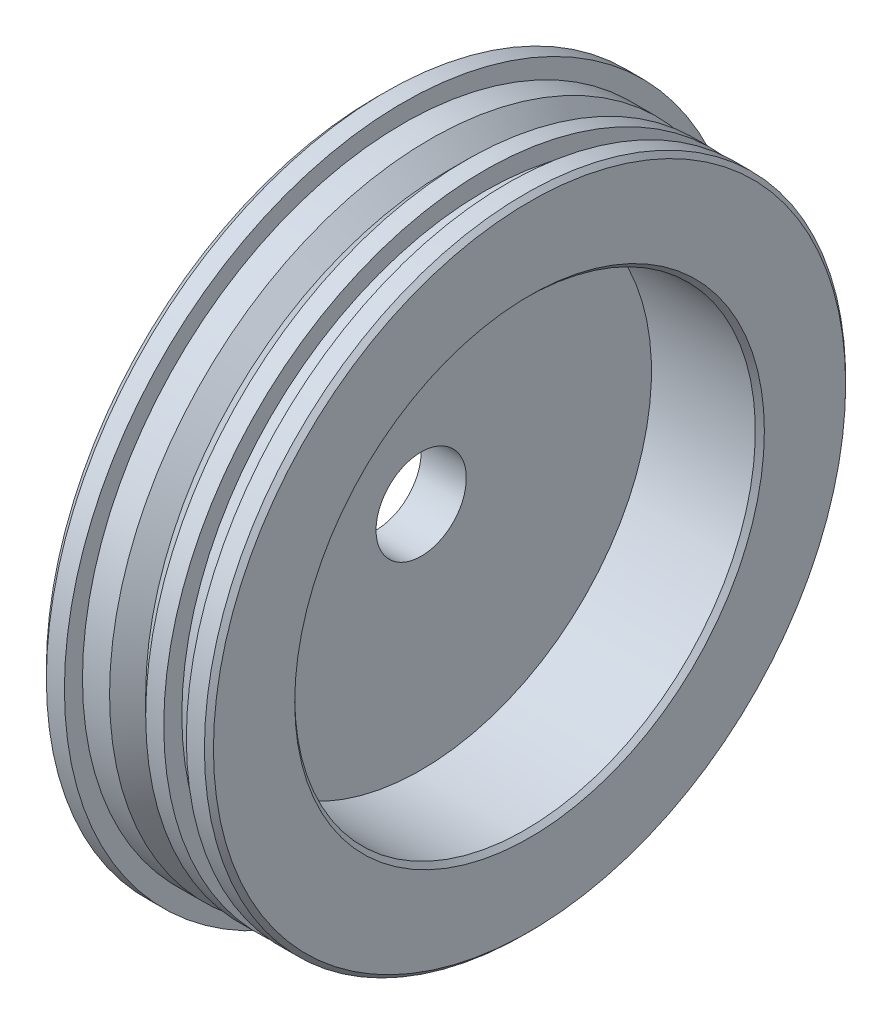
SolidWorks part; units mm, degrees
material "1060 Сплав"
ref_plane "Спереди" through (0, 0, 0) normal (0, 0, 1) x (1, 0, 0)
ref_plane "Сверху" through (0, 0, 0) normal (0, 1, 0) x (1, 0, 0)
ref_plane "Справа" through (0, 0, 0) normal (1, 0, 0) x (0, 0, -1)
sketch "Эскиз1" plane through (0, 0, 0) normal (0, 0, 1) x (1, 0, 0)
  line L0 (0, 0) -> (75.9362, 0) construction
  line L1 (-5, 0) -> (-5, 36.5)
  line L2 (-4, 37.5) -> (-2, 37.5)
  line L3 (-2, 37.5) -> (-2, 35.5)
  line L4 (-2, 35.5) -> (1, 35.5)
  line L5 (1, 35.5) -> (3, 33.5)
  line L6 (3, 33.5) -> (5, 35.5)
  line L7 (5, 35.5) -> (7, 35.5)
  line L8 (7, 35.5) -> (7, 33.5)
  line L9 (7, 33.5) -> (9.5, 33.5)
  line L10 (9.5, 33.5) -> (9.5, 35.5)
  line L11 (9.5, 35.5) -> (11.5, 35.5)
  line L12 (12, 35) -> (12, 26)
  line L13 (11.5, 25.5) -> (0, 25.5)
  line L14 (0, 25.5) -> (0, 0)
  line L15 (-5, 36.5) -> (-4, 37.5)
  line L16 (11.5, 35.5) -> (12, 35)
  line L17 (12, 26) -> (11.5, 25.5)
  line L18 (-5, 0) -> (0, 0)
  point P5 (-5, 37.5)
  point P16 (12, 35.5)
  point P17 (12, 25.5)
  dimension "D1" = 135
  dimension "D2" = 2
  dimension "D3" = 3
  dimension "D4" = 2.5
  dimension "D5" = 10
  dimension "D6" = 2
  dimension "D7" = 5
  dimension "D8" = 2
  dimension "D9" = 2.5
  dimension "D10" = 2
  dimension "D11" = 75
  dimension "D12" = 5
revolve "Повернуть1" add sketch "Эскиз1" angle 360 about L0
sketch "Эскиз2" plane through (-5, 0, 0) normal (-1, 0, 0) x (0, 0, 1)
  circle A0 centre (0, 0) radius 5
  dimension "D1" = 10
extrude "Вырез-Вытянуть1" cut sketch "Эскиз2" against normal blind 10
